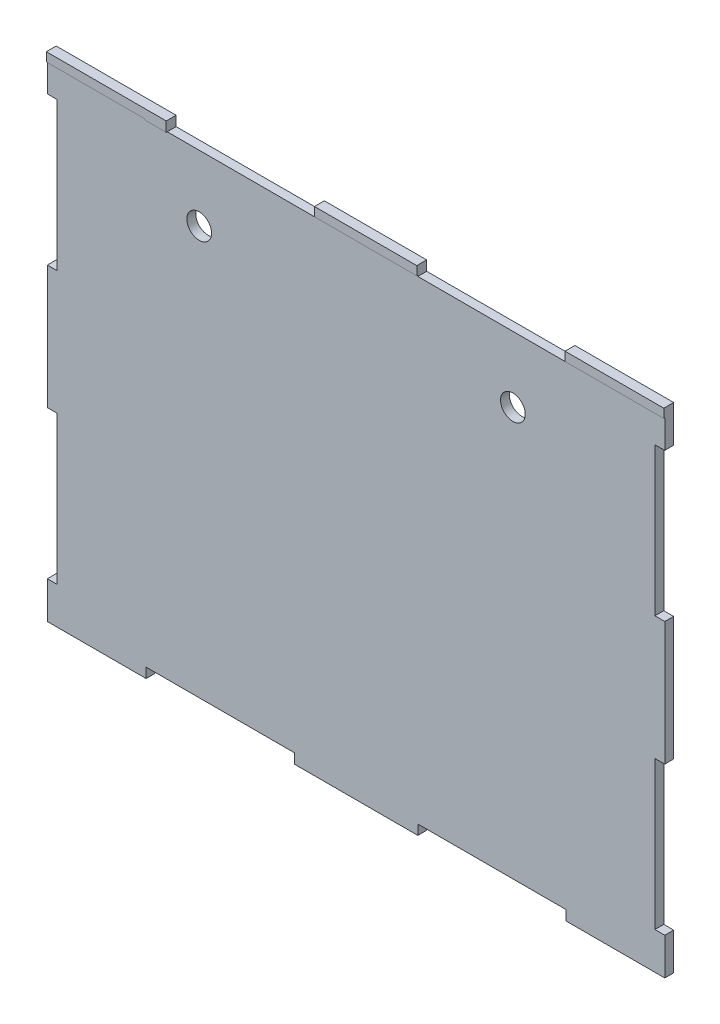
SolidWorks part; units mm, degrees
material "处理板，复杂型"
ref_plane "前视基准面" through (0, 0, 0) normal (0, 0, 1) x (1, 0, 0)
ref_plane "上视基准面" through (0, 0, 0) normal (0, 1, 0) x (1, 0, 0)
ref_plane "右视基准面" through (0, 0, 0) normal (1, 0, 0) x (0, 0, -1)
sketch "草图1" plane through (0, 0, 0) normal (0, 0, 1) x (1, 0, 0)
  line L0 (0, 389.8515) -> (0, -422.5248) construction
  line L1 (-125, 100) -> (125, 100)
  line L2 (-125, 100) -> (-125, -100)
  line L3 (-125, -100) -> (125, -100)
  line L4 (125, 100) -> (125, -100)
  dimension "D1" = 200
  dimension "D2" = 250
  dimension "D3" = 125
  dimension "D4" = 100
extrude "凸台-拉伸1" add sketch "草图1" along normal blind 3.6
sketch "草图2" plane through (0, 0, 3.6) normal (0, 0, 1) x (1, 0, 0)
  line L0 (-187.3662, 0) -> (197.8774, 0) construction
  line L1 (0, 153.4979) -> (0, -170.9485) construction
  line L2 (-121, 85) -> (-121, 25)
  line L5 (125, 85) -> (121, 85)
  line L6 (-125, 100) -> (-125, -100) construction
  line L7 (-125, 25) -> (-121, 25)
  line L9 (-125, -25) -> (-121, -25)
  line L11 (-125, 85) -> (-125, 25)
  line L12 (-125, -85) -> (-121, -85)
  line L16 (-125, 85) -> (-121, 85)
  line L20 (-121, -25) -> (-121, -85)
  line L21 (-125, -25) -> (-125, -85)
  line L22 (125, 85) -> (125, 25)
  line L23 (125, 25) -> (121, 25)
  line L24 (121, 85) -> (121, 25)
  line L25 (125, -25) -> (121, -25)
  line L26 (121, -25) -> (121, -85)
  line L27 (125, -85) -> (121, -85)
  line L28 (125, -25) -> (125, -85)
  dimension "D1" = 4
  dimension "D2" = 50
  dimension "D4" = 25
  dimension "D5" = 60
  dimension "D6" = 60
extrude "切除-拉伸1" cut sketch "草图2" against normal blind 10
sketch "草图3" plane through (0, 0, 3.6) normal (0, 0, 1) x (1, 0, 0)
  line L0 (-85, -96) -> (-25, -96)
  line L1 (0, 179.8057) -> (0, -208.2401) construction
  line L2 (-172.2789, 0) -> (195.6955, 0) construction
  line L4 (-125, -100) -> (125, -100) construction
  line L5 (25, -96) -> (85, -96)
  line L7 (-25, -96) -> (-25, -100)
  line L9 (25, -96) -> (25, -100)
  line L13 (-85, -96) -> (-85, -100)
  line L15 (85, -96) -> (85, -100)
  line L18 (-85, -100) -> (-25, -100)
  line L19 (25, -100) -> (85, -100)
  line L20 (25, 96) -> (25, 100)
  line L21 (25, 96) -> (85, 96)
  line L22 (85, 96) -> (85, 100)
  line L23 (25, 100) -> (85, 100)
  line L24 (-85, 96) -> (-85, 100)
  line L25 (-85, 96) -> (-25, 96)
  line L26 (-25, 96) -> (-25, 100)
  line L27 (-85, 100) -> (-25, 100)
  dimension "D1" = 4
  dimension "D2" = 50
  dimension "D5" = 25
  dimension "D6" = 60
  dimension "D7" = 60
extrude "切除-拉伸2" cut sketch "草图3" against normal blind 10
sketch "草图4" plane through (0, 0, 0) normal (0, 0, -1) x (-1, 0, 0)
  circle A0 centre (-63.5, 69.4) radius 5
  circle A1 centre (63.5, 69.4) radius 5
extrude "切除-拉伸3" cut sketch "草图4" against normal blind 10
sketch "草图5" plane through (0, 0, 0) normal (0, 0, -1) x (-1, 0, 0)
  line L0 (125, 100) -> (125, 85) construction
  line L1 (-125, 100) -> (125, 100)
  line L2 (-125, 100) -> (-125, 96.4)
  line L3 (-125, 96.4) -> (125, 96.4)
  line L4 (125, 100) -> (125, 96.4)
extrude "凸台-拉伸2" add sketch "草图5" against normal blind 4
sketch "草图6" plane through (0, 0, 0) normal (0, 0, -1) x (-1, 0, 0)
  line L0 (-125, 100) -> (125, 100) construction
  line L1 (-85, 96) -> (-25, 96)
  line L2 (-85, 96) -> (-85, 100)
  line L3 (-85, 100) -> (-25, 100)
  line L4 (-25, 96) -> (-25, 100)
  line L5 (125, 100) -> (-125, 100) construction
  line L7 (25, 96) -> (85, 96)
  line L8 (25, 96) -> (25, 100)
  line L9 (25, 100) -> (85, 100)
  line L10 (85, 96) -> (85, 100)
extrude "切除-拉伸4" cut sketch "草图6" against normal through all
sketch "草图7" plane through (-85, 0, 0) normal (1, 0, 0) x (0, 0, -1)
  line L1 (-4, 96.4) -> (0, 96.4)
  line L2 (-4, 96.4) -> (-4, 100)
  line L3 (-4, 100) -> (0, 100)
  line L4 (0, 96.4) -> (0, 100)
extrude "凸台-拉伸3" add sketch "草图7" along normal blind 8.5
sketch "草图8" plane through (0, 0, 0) normal (0, 0, -1) x (-1, 0, 0)
  line L0 (76.5, 100) -> (125, 100) construction
  line L1 (16.4485, 96.4) -> (84.9868, 96.4)
  line L2 (16.4485, 96.4) -> (16.4485, 100)
  line L3 (16.4485, 100) -> (84.9868, 100)
  line L4 (84.9868, 96.4) -> (84.9868, 100)
extrude "切除-拉伸5" cut sketch "草图8" against normal blind 8.5
sketch "草图9" plane through (0, 0, 0) normal (0, 0, -1) x (-1, 0, 0)
  line L0 (85, 96) -> (25, 96) construction
  line L1 (84.9868, 100) -> (76.4485, 100)
  line L2 (84.9868, 100) -> (84.9868, 96)
  line L3 (84.9868, 96) -> (76.4485, 96)
  line L4 (76.4485, 100) -> (76.4485, 96)
extrude "凸台-拉伸4" add sketch "草图9" against normal blind 4
sketch "草图10" plane through (0, 0, 0) normal (0, 0, -1) x (-1, 0, 0)
  line L1 (76.4485, 100) -> (16.4485, 100)
  line L2 (76.4485, 100) -> (76.4485, 96)
  line L3 (76.4485, 96) -> (16.4485, 96)
  line L4 (16.4485, 100) -> (16.4485, 96)
extrude "切除-拉伸6" cut sketch "草图10" against normal blind 8.5
